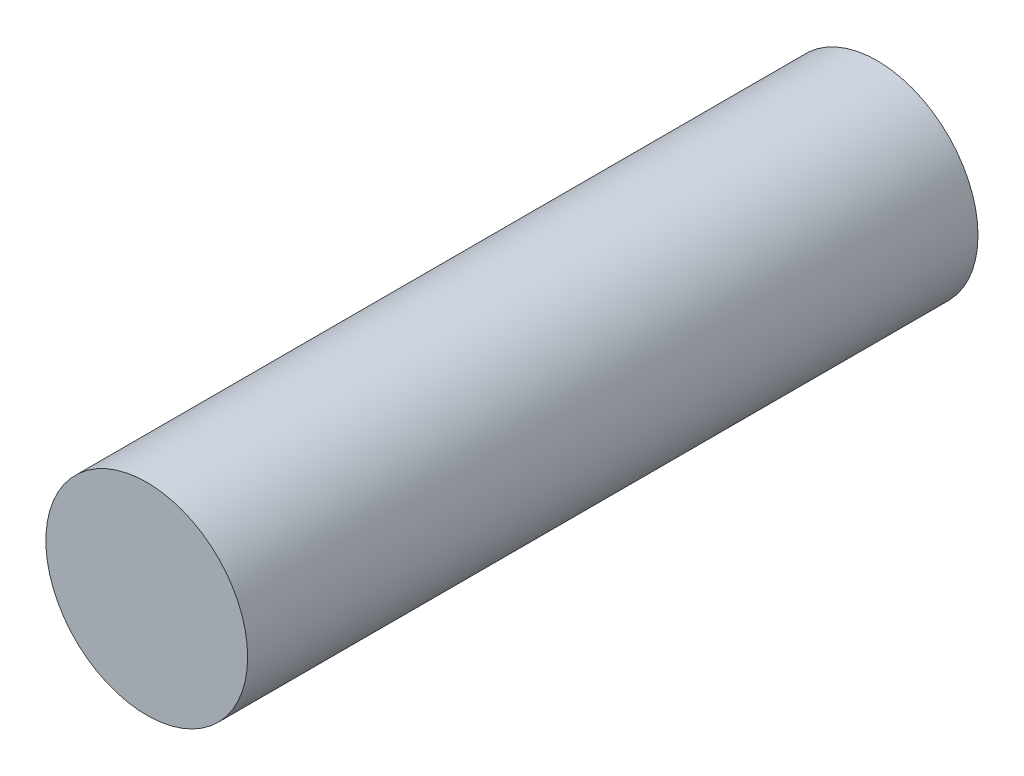
SolidWorks part; units mm, degrees
other "标注1"
sketch "草图2" plane through (52.5, 52.5, 380) normal (0.9186, 0.3495, 0.1845) x (0.3153, -0.3666, -0.8753)
ref_plane "前视基准面" through (0, 0, 0) normal (0, 0, 1) x (1, 0, 0)
ref_plane "上视基准面" through (0, 0, 0) normal (0, 1, 0) x (1, 0, 0)
ref_plane "右视基准面" through (0, 0, 0) normal (1, 0, 0) x (0, 0, -1)
other "Configuration Table"
sketch "草图1" plane through (0, 0, 0) normal (0, 0, 1) x (1, 0, 0)
  circle A0 centre (0, 0) radius 52.5
  dimension "D1" = 105
extrude "凸台-拉伸1" add sketch "草图1" along normal blind 380
